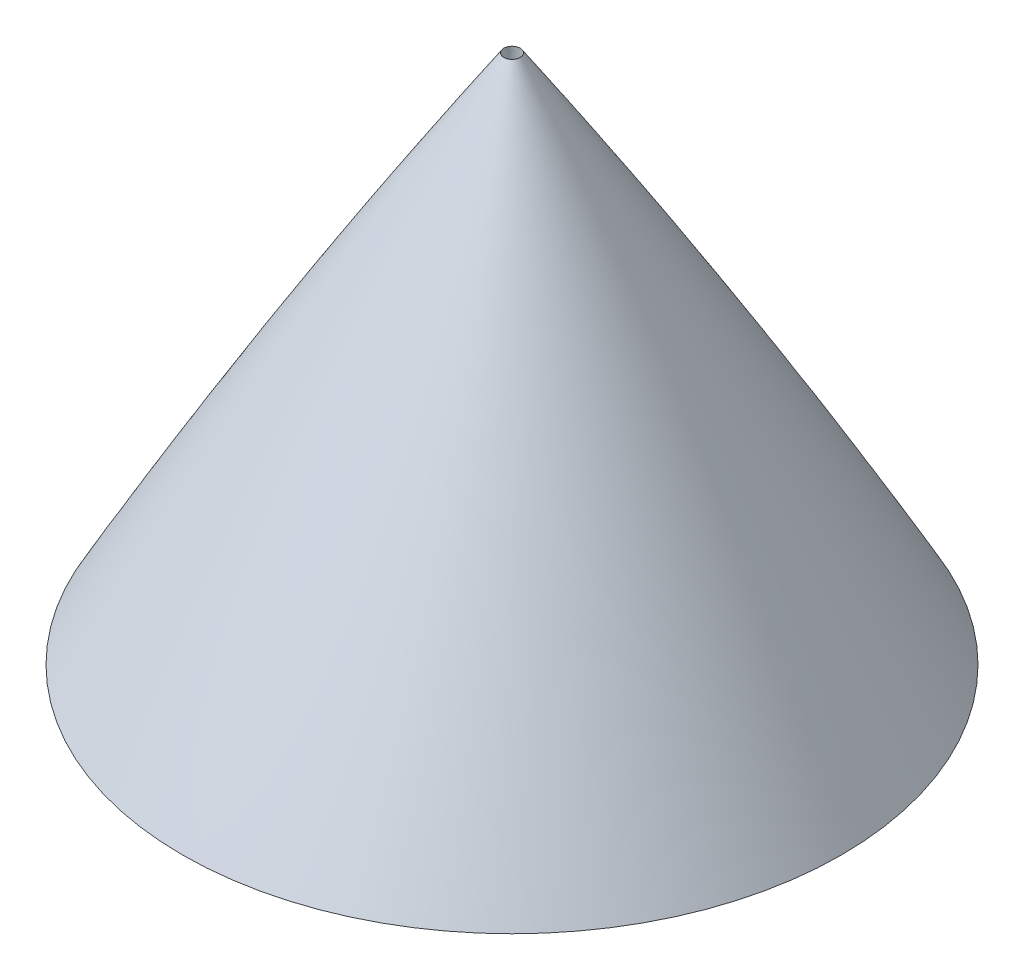
SolidWorks part; units mm, degrees
material "1060 Alloy"
ref_plane "Front Plane" through (0, 0, 0) normal (0, 0, 1) x (1, 0, 0)
ref_plane "Top Plane" through (0, 0, 0) normal (0, 1, 0) x (1, 0, 0)
ref_plane "Right Plane" through (0, 0, 0) normal (1, 0, 0) x (0, 0, -1)
sketch "Sketch1" plane through (0, 0, 0) normal (0, 0, 1) x (1, 0, 0)
  line L0 (75.6855, -0.3445) -> (75.6855, 149.6555)
  line L2 (65.6855, -0.3445) -> (65.6855, 149.6555)
  line L4 (65.6855, -0.3445) -> (75.6855, -0.3445)
  line L5 (0.4588, 400) -> (0.4375, 381.3992)
  line L6 (0, -198.8179) -> (0, -350.074)
  spline S0 degree 4 poles (-14.6369, 421.4741) (-14.3057, 421.0307) (-13.6445, 420.1427) (-12.6566, 418.8067) (-11.3495, 417.0212) (-10.0545, 415.2335) (-8.7788, 413.4552) (-7.5081, 411.6645) (-6.2702, 409.9039) (-5.0044, 408.0824) (-3.8189, 406.3634) (-2.4998, 404.4234) (-1.4735, 402.9077) (0.0393, 400.6358) (0.7278, 399.5946) (1.9701, 397.7006) (2.9368, 396.2112) (3.9026, 394.7101) (4.8801, 393.1784) (5.844, 391.6542) (6.8034, 390.1239) (7.7618, 388.5814) (8.7192, 387.0267) (16.6466, 374.037) (28.2573, 353.0149) (42.102, 323.2587) (56.6108, 282.3312) (67.0596, 242.0803) (72.3341, 209.22) (74.5835, 183.9236) (75.2731, 169.1734) (75.3973, 165.9556) (75.4848, 163.2083) (75.5353, 161.393) (75.5784, 159.5874) (75.6143, 157.7843) (75.643, 155.9674) (75.6646, 154.1829) (75.6789, 152.4065) (75.6865, 150.1399) (75.6859, 148.8889) (75.6759, 146.1484) (75.6549, 144.3126) (75.6234, 141.9551) (75.5814, 139.8598) (75.5289, 137.6322) (75.4659, 135.4723) (75.3921, 133.2683) (75.3073, 131.0723) (75.2114, 128.8575) (75.1041, 126.638) (75.0155, 124.9717) (74.9528, 123.8618) (74.9206, 123.3069) knots 0 0 0 0 0 0.006969 0.013937 0.020906 0.027875 0.034717 0.04156 0.048403 0.055246 0.062088 0.068931 0.075774 0.082616 0.0883 0.093983 0.099666 0.10535 0.111033 0.116716 0.122399 0.128083 0.133891 0.1397 0.313954 0.430124 0.546294 0.685698 0.836718 0.848335 0.865761 0.871569 0.877253 0.882936 0.888619 0.894302 0.899986 0.905669 0.911352 0.917035 0.923907 0.930779 0.93765 0.944522 0.951393 0.958265 0.965136 0.972008 0.979006 0.986004 0.993002 1 1 1 1 1 construction
  spline S1 degree 4 poles (0.4588, 400) (0.6665, 399.6857) (1.0836, 399.0522) (1.9701, 397.7006) (2.9368, 396.2112) (3.9026, 394.7101) (4.8801, 393.1784) (5.844, 391.6542) (6.8034, 390.1239) (7.7618, 388.5814) (8.7192, 387.0267) (16.6466, 374.037) (28.2573, 353.0149) (42.102, 323.2587) (56.6108, 282.3312) (67.0596, 242.0803) (72.3341, 209.22) (74.5835, 183.9236) (75.2731, 169.1734) (75.3973, 165.9556) (75.4848, 163.2083) (75.5353, 161.393) (75.5784, 159.5874) (75.6143, 157.7843) (75.643, 155.9674) (75.6646, 154.1829) (75.6789, 152.4065) (75.6843, 150.791) (75.6855, 150.0323) (75.6855, 149.6555) knots 0.082616 0.082616 0.082616 0.082616 0.082616 0.0883 0.093983 0.099666 0.10535 0.111033 0.116716 0.122399 0.128083 0.133891 0.1397 0.313954 0.430124 0.546294 0.685698 0.836718 0.848335 0.865761 0.871569 0.877253 0.882936 0.888619 0.894302 0.899986 0.905669 0.911352 0.917035 0.917035 0.917035 0.917035 0.917035
  spline S2 degree 1 poles (-7.8848, 394.4879) (65.6855, 149.6555) knots 0 0 1 1 construction
  spline S3 degree 3 poles (-7.8848, 394.4879) (-7.7214, 394.2405) (-7.4207, 393.784) (-6.8189, 392.8667) (-6.2109, 391.936) (-5.656, 391.0813) (-5.1151, 390.2438) (-4.3899, 389.1152) (-3.1128, 387.1137) (-1.3199, 384.26) (2.9308, 377.3566) (11.7925, 362.1999) (29.0792, 328.5343) (48.4086, 277.9338) (60.1725, 225.0599) (64.306, 187.4419) (65.2667, 169.911) (65.5254, 161.808) (65.6023, 158.4387) (65.6401, 156.0647) (65.657, 154.7234) (65.6674, 153.7264) (65.6755, 152.7071) (65.6813, 151.5956) (65.6848, 150.4988) (65.6855, 149.952) (65.6855, 149.6555) knots 0.082616 0.082616 0.082616 0.082616 0.085876 0.089135 0.092395 0.095654 0.098914 0.102173 0.108692 0.12173 0.134768 0.186919 0.291221 0.499826 0.708431 0.812733 0.864884 0.877922 0.89096 0.897479 0.900738 0.903998 0.907257 0.910517 0.913776 0.917035 0.917035 0.917035 0.917035 only from (0.4375, 381.3992) to (65.6855, 149.6555)
  point P11 (0.4588, 400)
  dimension "D1" = 400
  dimension "D2" = 150
  dimension "D3" = 150
  dimension "D4" = 10
revolve "Revolve3" add sketch "Sketch1" angle 360 about L6
ref_plane "Plane1" through (0, 149.6555, 0) normal (0, 1, 0) x (1, 0, 0)
sketch "Sketch2" plane through (0, 149.6555, 0) normal (0, 1, 0) x (1, 0, 0)
  circle A0 centre (0, 0) radius 65.6855 construction
  circle A1 centre (0, 0) radius 65.6855
  circle A2 centre (0, 0) radius 57.6855
  dimension "D1" = 8
extrude "Boss-Extrude1" add sketch "Sketch2" against normal blind 300
ref_plane "Plane2" through (0, 400, 0) normal (0, -1, 0) x (-1, 0, 0)
ref_plane "Plane4" through (0, 370, 0) normal (0, -1, 0) x (-1, 0, 0)
sketch "Sketch3" plane through (0, 370, 0) normal (0, -1, 0) x (-1, 0, 0)
  circle A0 centre (0, 0) radius 120.7266
extrude "Cut-Extrude1" cut sketch "Sketch3" along normal through all
